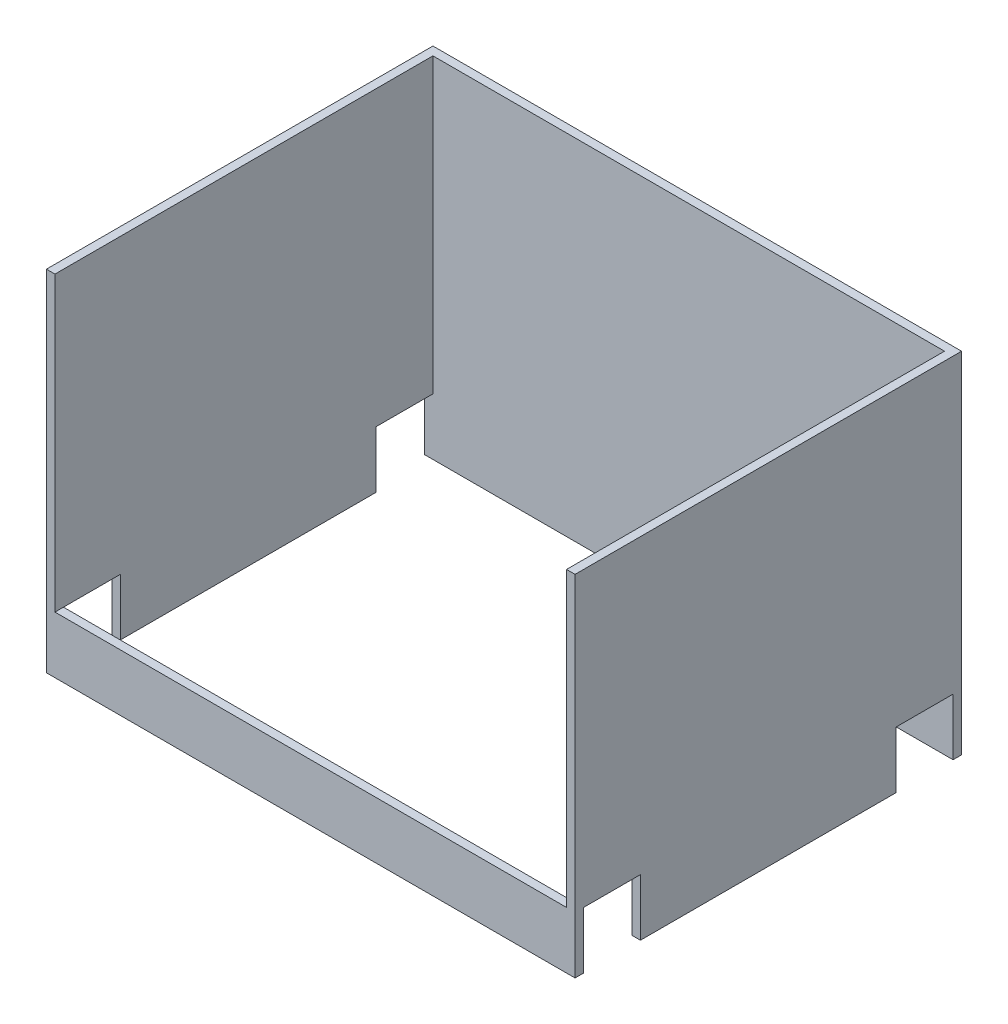
SolidWorks part; units mm, degrees
ref_plane "Front Plane" through (0, 0, 0) normal (0, 0, 1) x (1, 0, 0)
ref_plane "Top Plane" through (0, 0, 0) normal (0, 1, 0) x (1, 0, 0)
ref_plane "Right Plane" through (0, 0, 0) normal (1, 0, 0) x (0, 0, -1)
sketch "Sketch2" plane through (0, 0, 0) normal (0, 1, 0) x (1, 0, 0)
  line L1 (-60, -60) -> (60, -60)
  line L2 (-60, -60) -> (-60, 60)
  line L3 (-60, 60) -> (60, 60)
  line L4 (60, -60) -> (60, 60)
  line L5 (-60, -60) -> (60, 60) construction
  line L6 (-60, 60) -> (60, -60) construction
  line L7 (-60, 60) -> (-90, 60)
  line L8 (-60, 60) -> (-60, -60)
  line L9 (-60, -60) -> (-90, -60)
  line L10 (-90, 60) -> (-90, -60)
  line L15 (-93, 68) -> (93, 68)
  line L16 (-93, 68) -> (-93, -68)
  line L17 (-93, -68) -> (93, -68)
  line L18 (93, 68) -> (93, -68)
  line L27 (60, 60) -> (90, 60)
  line L28 (60, 60) -> (60, -60)
  line L29 (60, -60) -> (90, -60)
  line L30 (90, 60) -> (90, -60)
  line L31 (-90, 60) -> (90, 60)
  line L32 (-90, 60) -> (-90, 65)
  line L33 (-90, 65) -> (90, 65)
  line L34 (90, 60) -> (90, 65)
  line L35 (-90, -60) -> (90, -60)
  line L36 (-90, -60) -> (-90, -65)
  line L37 (-90, -65) -> (90, -65)
  line L38 (90, -60) -> (90, -65)
  point P0 (0, 0)
  dimension "D1" = 120
  dimension "D2" = 120
  dimension "D3" = 30
  dimension "D4" = 8
  dimension "D5" = 8
  dimension "D6" = 30
  dimension "D7" = 3
  dimension "D8" = 3
  dimension "D9" = 3
  dimension "D10" = 3
extrude "Boss-Extrude1" add sketch "Sketch2" against normal blind 20
sketch "Sketch3" plane through (0, 0, 0) normal (0, 1, 0) x (1, 0, 0)
  line L1 (-93, -68) -> (-90, -68)
  line L2 (-93, -68) -> (-93, 65)
  line L3 (-93, 65) -> (-90, 65)
  line L4 (-90, -68) -> (-90, 65)
  line L5 (93, -68) -> (90, -68)
  line L6 (93, -68) -> (93, 65)
  line L7 (93, 65) -> (90, 65)
  line L8 (90, -68) -> (90, 65)
  line L9 (93, 68) -> (-93, 68)
  line L10 (93, 68) -> (93, 65)
  line L11 (93, 65) -> (-93, 65)
  line L12 (-93, 68) -> (-93, 65)
  line M1 (93, -68) -> (93, 68)
  line M2 (93, 68) -> (-93, 68)
  line M3 (-93, 68) -> (-93, -68)
  line M4 (-93, -68) -> (93, -68)
  line M5 (90, 65) -> (90, -65)
  line M7 (-90, -65) -> (-90, 65)
  line M8 (-90, 65) -> (90, 65)
extrude "Boss-Extrude2" add sketch "Sketch3" along normal blind 103 contours L4 L3 M4 M7 M3 | L7 L3 M1 M2 M3 M8 | L8 L7 M4 M1 M5
sketch "Sketch4" plane through (93, 0, 0) normal (1, 0, 0) x (0, 0, -1)
  line L0 (0, 0) -> (0, -20) construction
  line L1 (-65, -20) -> (-45, -20)
  line L2 (-65, -20) -> (-65, 0)
  line L3 (-65, 0) -> (-45, 0)
  line L4 (-45, -20) -> (-45, 0)
  line L5 (68, -20) -> (-68, -20) construction
  line L6 (65, 0) -> (45, 0)
  line L7 (45, -20) -> (45, 0)
  line L8 (65, -20) -> (45, -20)
  line L9 (65, -20) -> (65, 0)
  dimension "D1" = 20
  dimension "D2" = 20
extrude "Cut-Extrude1" cut sketch "Sketch4" against normal through all both and the other way through all
